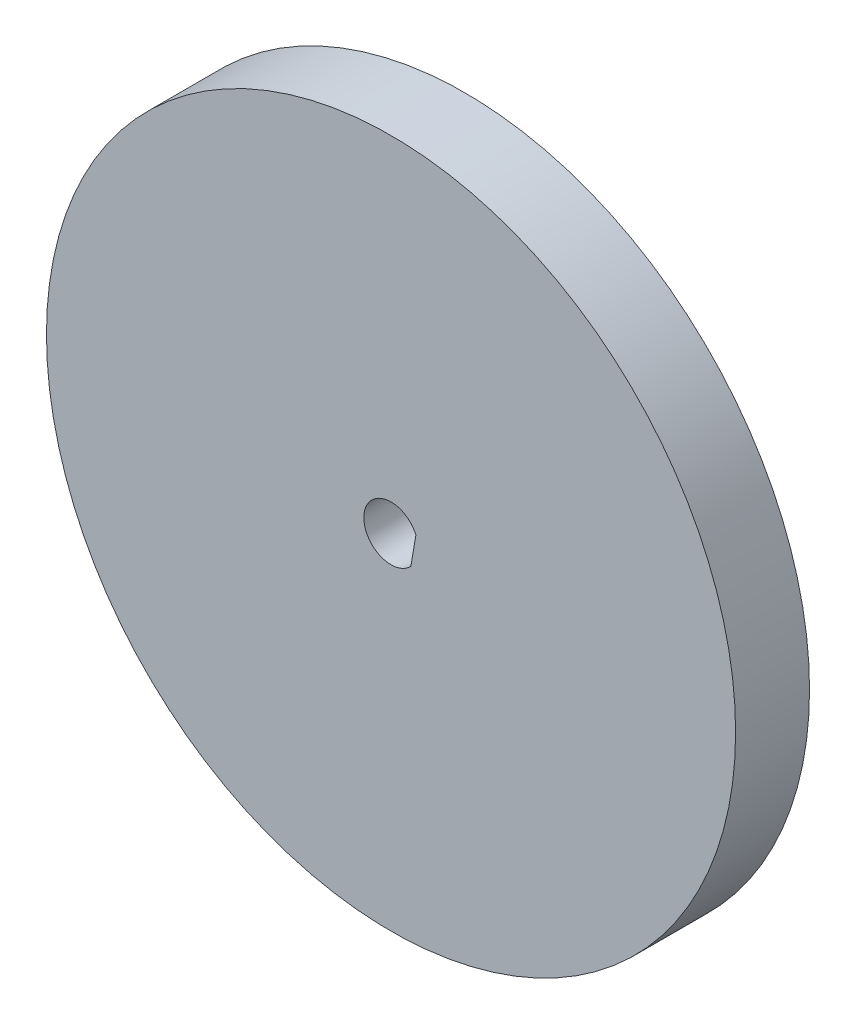
SolidWorks part; units mm, degrees
ref_plane "Front Plane" through (0, 0, 0) normal (0, 0, 1) x (1, 0, 0)
ref_plane "Top Plane" through (0, 0, 0) normal (0, 1, 0) x (1, 0, 0)
ref_plane "Right Plane" through (0, 0, 0) normal (1, 0, 0) x (0, 0, -1)
sketch "Sketch1" plane through (0, 0, 0) normal (0, 0, 1) x (1, 0, 0)
  circle A0 centre (-10.9917, 10.7964) radius 38
  dimension "D1" = 76
extrude "Boss-Extrude1" add sketch "Sketch1" along normal blind 8.1534
sketch "Sketch3" plane through (0, 0, 8.1534) normal (0, 0, 1) x (1, 0, 0)
  line L0 (-8.527, 10.3777) -> (-8.2493, 12.0126) construction
  line L1 (-8.8047, 8.7428) -> (-8.527, 10.3777) construction
  line L2 (-8.527, 10.3777) -> (-8.2493, 12.0126)
  line L3 (-8.8047, 8.7428) -> (-8.527, 10.3777)
  arc A0 (-8.2493, 12.0126) -> (-8.8047, 8.7428) centre (-10.9917, 10.7964) ccw construction
  arc A1 (-8.2493, 12.0126) -> (-8.8047, 8.7428) centre (-10.9917, 10.7964) ccw
extrude "Cut-Extrude1" cut sketch "Sketch3" against normal through all
equation "\"MDF\"= .321in"
equation "\"Foamcore\"= .13in"
equation "\"Gmaterial\"= \"MDF\""
equation "\"D1@Boss-Extrude1\"=\"MDF\""
